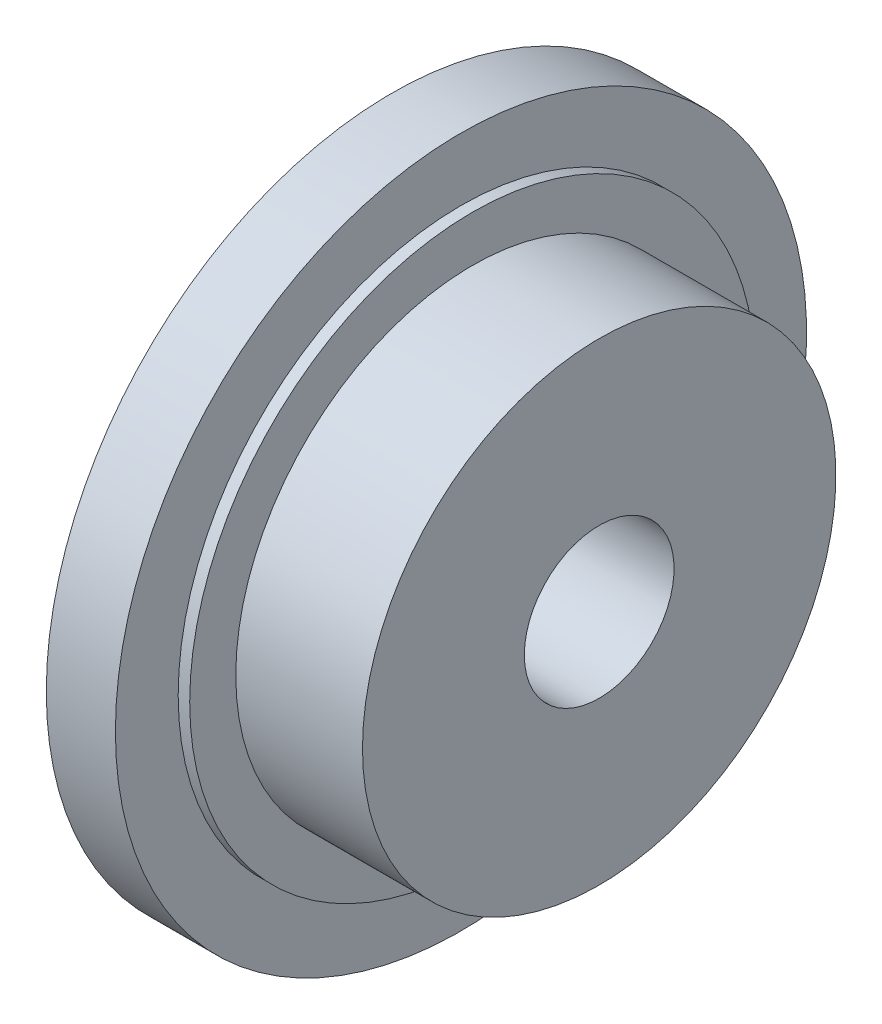
SolidWorks part; units mm, degrees
ref_plane "Front Plane" through (0, 0, 0) normal (0, 0, 1) x (1, 0, 0)
ref_plane "Top Plane" through (0, 0, 0) normal (0, 1, 0) x (1, 0, 0)
ref_plane "Right Plane" through (0, 0, 0) normal (1, 0, 0) x (0, 0, -1)
sketch "Sketch1" plane through (0, 0, 0) normal (0, 0, 1) x (1, 0, 0)
  line L0 (0, 30) -> (6, 30)
  line L9 (6, 30) -> (6, 24.55)
  line L10 (6, 24.55) -> (7, 24.55)
  line L11 (7, 24.55) -> (7, 20.55)
  line L12 (7, 20.55) -> (18, 20.55)
  line L13 (18, 20.55) -> (18, 6.5)
  line L14 (18, 6.5) -> (6, 6.5)
  line L15 (6, 6.5) -> (6, 7.5)
  line L16 (6, 7.5) -> (0, 7.5)
  line L17 (0, 7.5) -> (0, 30)
  line L18 (0, 0) -> (18, 0) construction
  dimension "D1" = 6
  dimension "D2" = 12
  dimension "D3" = 1
  dimension "D4" = 6
  dimension "D5" = 4
  dimension "D6" = 7.5
  dimension "D7" = 30
  dimension "D8" = 14.05
  dimension "D9" = 6.5
revolve "Revolve1" add sketch "Sketch1" angle 360 about L18
sketch "Sketch2" plane through (0, 0, 0) normal (-1, 0, 0) x (0, 0, 1)
  circle A0 centre (0, 0) radius 20 construction
  circle A1 centre (0, 20) radius 2.5
  circle A2 centre (17.3205, 10) radius 2.5
  circle A3 centre (17.3205, -10) radius 2.5
  circle A4 centre (0, -20) radius 2.5
  circle A5 centre (-17.3205, -10) radius 2.5
  circle A6 centre (-17.3205, 10) radius 2.5
  point P18 (0, 0)
  dimension "D1" = 40
  dimension "D2" = 5
extrude "Cut-Extrude1" cut sketch "Sketch2" against normal blind 4.5
sketch "Sketch3" plane through (18, 0, 0) normal (1, 0, 0) x (0, 0, -1)
  circle A0 centre (0, 0) radius 12 construction
  circle A3 centre (0, 12) radius 3.3
  circle A6 centre (11.4127, 3.7082) radius 3.3
  circle A7 centre (7.0534, -9.7082) radius 3.3
  circle A8 centre (-7.0534, -9.7082) radius 3.3
  circle A9 centre (-11.4127, 3.7082) radius 3.3
  point P15 (0, 0)
  dimension "D1" = 24
  dimension "D2" = 6.6
extrude "Cut-Extrude2" [suppressed] cut sketch "Sketch3" against normal blind 10.5
chamfer "Chamfer1" [suppressed] distance 1 angle 45
sketch "Sketch4" plane through (0, 0, 0) normal (-1, 0, 0) x (0, 0, 1)
  circle A0 centre (0, 0) radius 8.5
  dimension "D1" = 17
extrude "Cut-Extrude3" cut sketch "Sketch4" against normal blind 2
equation "\"R_ROLL\"= 5mm"
equation "\"D_SUN\"= 80mm"
equation "\"NUM_ROLL\"= 16"
equation "\"RHO\"= 1mm"
equation "\"D_SHAFT\"= 15mm"
equation "\"D_OUTPUT\"= 40mm"
equation "\"NUM_OUT\"= 6"
equation "\"R_OUT_ROLL\"= 5mm"
equation "\"D1@Sketch2\"=\"D_OUTPUT\""
